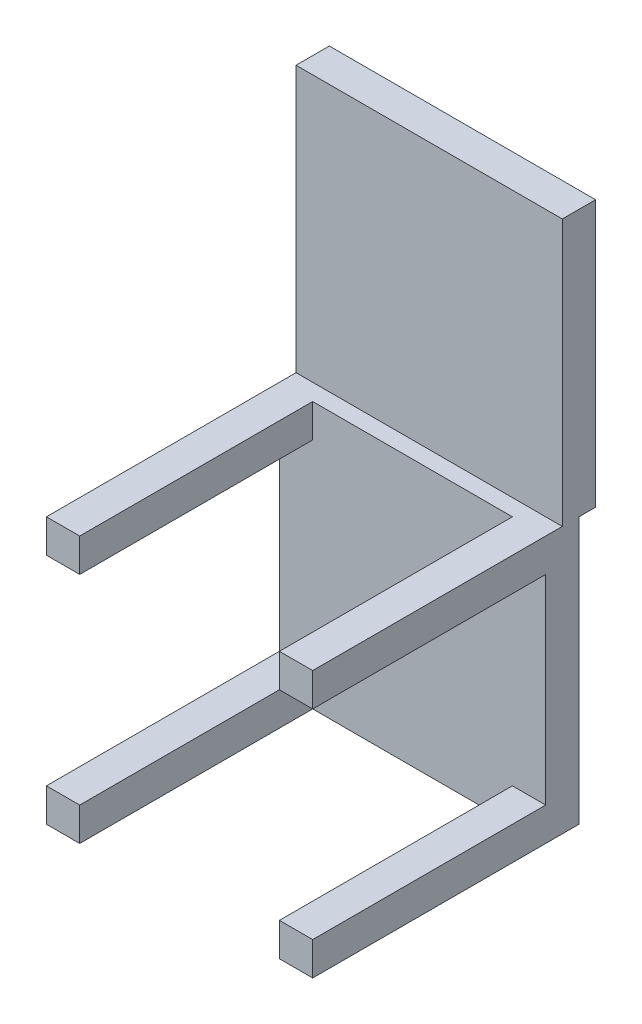
SolidWorks part; units mm, degrees
ref_plane "前视基准面" through (0, 0, 0) normal (0, 0, 1) x (1, 0, 0)
ref_plane "上视基准面" through (0, 0, 0) normal (0, 1, 0) x (1, 0, 0)
ref_plane "右视基准面" through (0, 0, 0) normal (1, 0, 0) x (0, 0, -1)
other "Configuration Table"
sketch "草图1" plane through (0, 0, 0) normal (0, 0, 1) x (1, 0, 0)
  line L1 (-200, -200) -> (200, -200)
  line L2 (-200, -200) -> (-200, 200)
  line L3 (-200, 200) -> (200, 200)
  line L4 (200, -200) -> (200, 200)
  line L5 (-200, -200) -> (200, 200) construction
  line L6 (-200, 200) -> (200, -200) construction
  point P0 (0, 0)
extrude "凸台-拉伸1" add sketch "草图1" along normal blind 50
sketch "草图2" plane through (0, 0, 0) normal (0, 0, 1) x (1, 0, 0)
  line L1 (150, 150) -> (200, 150)
  line L2 (150, 150) -> (150, 200)
  line L3 (150, 200) -> (200, 200)
  line L4 (200, 150) -> (200, 200)
  line L5 (150, 150) -> (200, 200) construction
  line L6 (150, 200) -> (200, 150) construction
  point P0 (175, 175)
extrude "凸台-拉伸2" add sketch "草图2" along normal blind 400
sketch "草图3" plane through (0, 0, 0) normal (0, 0, 1) x (1, 0, 0)
  line L0 (200, 200) -> (-200, 200) construction
  line L1 (-200, 150) -> (-150, 150)
  line L2 (-200, 150) -> (-200, 200)
  line L3 (-200, 200) -> (-150, 200)
  line L4 (-150, 150) -> (-150, 200)
  line L5 (-200, 150) -> (-150, 200) construction
  line L6 (-200, 200) -> (-150, 150) construction
  point P0 (-175, 175)
extrude "凸台-拉伸3" add sketch "草图3" along normal blind 400
sketch "草图4" plane through (0, 0, 0) normal (0, 0, 1) x (1, 0, 0)
  line L0 (200, -200) -> (200, 200) construction
  line L1 (150, -200) -> (200, -200)
  line L2 (150, -200) -> (150, -150)
  line L3 (150, -150) -> (200, -150)
  line L4 (200, -200) -> (200, -150)
  line L5 (150, -200) -> (200, -150) construction
  line L6 (150, -150) -> (200, -200) construction
  point P0 (175, -175)
extrude "凸台-拉伸4" add sketch "草图4" along normal blind 400
sketch "草图5" plane through (0, 0, 0) normal (0, 0, 1) x (1, 0, 0)
  line L1 (-200, -200) -> (-150, -200)
  line L2 (-200, -200) -> (-200, -150)
  line L3 (-200, -150) -> (-150, -150)
  line L4 (-150, -200) -> (-150, -150)
  line L5 (-200, -200) -> (-150, -150) construction
  line L6 (-200, -150) -> (-150, -200) construction
  point P0 (-175, -175)
extrude "凸台-拉伸5" add sketch "草图5" along normal blind 400
sketch "草图6" plane through (0, 0, 0) normal (0, 0, 1) x (1, 0, 0)
  line L1 (-200, -200) -> (200, -200)
  line L2 (-200, -200) -> (-200, 200)
  line L3 (-200, 200) -> (200, 200)
  line L4 (200, -200) -> (200, 200)
  line L5 (-200, -200) -> (200, 200) construction
  line L6 (-200, 200) -> (200, -200) construction
  point P0 (0, 0)
extrude "凸台-拉伸6" add sketch "草图6" along normal blind 50
sketch "草图7" plane through (0, 200, 0) normal (0, 1, 0) x (1, 0, 0)
  line L1 (-200, -25) -> (200, -25)
  line L2 (-200, -25) -> (-200, 25)
  line L3 (-200, 25) -> (200, 25)
  line L4 (200, -25) -> (200, 25)
  line L5 (-200, -25) -> (200, 25) construction
  line L6 (-200, 25) -> (200, -25) construction
  point P0 (0, 0)
extrude "凸台-拉伸7" add sketch "草图7" along normal blind 400
